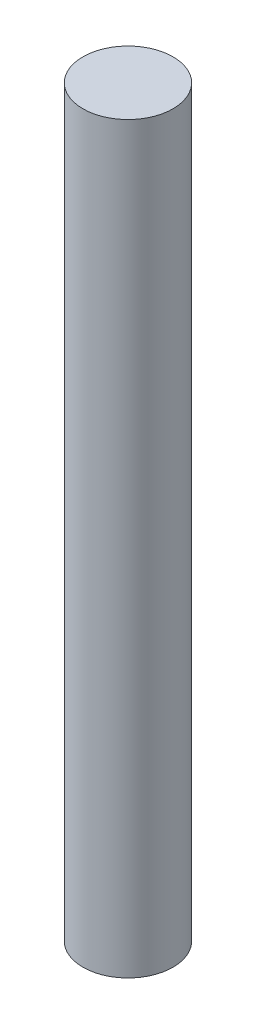
SolidWorks part; units mm, degrees
ref_plane "Front Plane" through (0, 0, 0) normal (0, 0, 1) x (1, 0, 0)
ref_plane "Top Plane" through (0, 0, 0) normal (0, 1, 0) x (1, 0, 0)
ref_plane "Right Plane" through (0, 0, 0) normal (1, 0, 0) x (0, 0, -1)
sketch "Sketch2" plane through (0, 0, 0) normal (0, 1, 0) x (1, 0, 0)
  circle A0 centre (0, 0) radius 4
  dimension "D1" = 8
extrude "Boss-Extrude1" add sketch "Sketch2" along normal mid plane 66 contours A0
